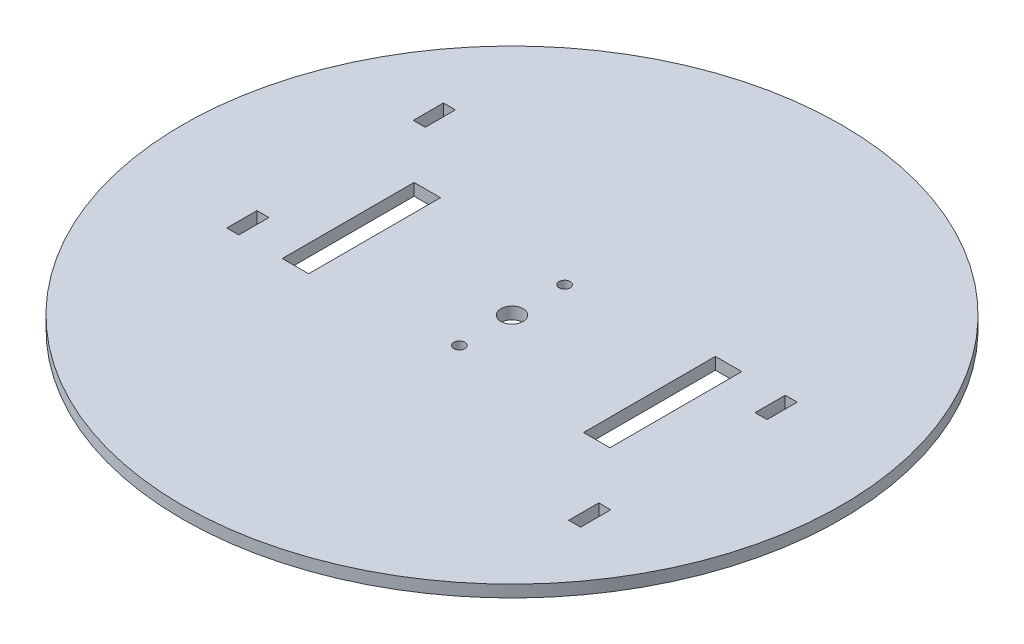
SolidWorks part; units mm, degrees
ref_plane "Front Plane" through (0, 0, 0) normal (0, 0, 1) x (1, 0, 0)
ref_plane "Top Plane" through (0, 0, 0) normal (0, 1, 0) x (1, 0, 0)
ref_plane "Right Plane" through (0, 0, 0) normal (1, 0, 0) x (0, 0, -1)
sketch "Sketch1" plane through (0, 0, 0) normal (0, 1, 0) x (1, 0, 0)
  circle A0 centre (0, 0) radius 87.5
  dimension "D1" = 175
extrude "Boss-Extrude1" add sketch "Sketch1" along normal blind 3.18
sketch "Sketch2" plane through (0, 3.18, 0) normal (0, 1, 0) x (1, 0, 0)
  line L0 (-40, 0) -> (40, 0) construction
  line L2 (0, 58.7688) -> (0, -27.7699) construction
  line L3 (-43.5, 17.5) -> (-36.5, 17.5)
  line L4 (-43.5, 17.5) -> (-43.5, -17.5)
  line L5 (-43.5, -17.5) -> (-36.5, -17.5)
  line L6 (-36.5, 17.5) -> (-36.5, -17.5)
  line L7 (-43.5, 17.5) -> (-36.5, -17.5) construction
  line L8 (-43.5, -17.5) -> (-36.5, 17.5) construction
  line L9 (36.5, 17.5) -> (43.5, 17.5)
  line L10 (36.5, 17.5) -> (36.5, -17.5)
  line L11 (36.5, -17.5) -> (43.5, -17.5)
  line L12 (43.5, 17.5) -> (43.5, -17.5)
  line L13 (36.5, 17.5) -> (43.5, -17.5) construction
  line L14 (36.5, -17.5) -> (43.5, 17.5) construction
  circle A0 centre (0, 0) radius 87.5 construction
  point P13 (-87.5, 0)
  point P14 (87.5, 0)
  dimension "D1" = 80
  dimension "D2" = 7
  dimension "D3" = 7
  dimension "D4" = 35
  dimension "D5" = 35
extrude "Cut-Extrude1" cut sketch "Sketch2" against normal blind 3.18
sketch "Sketch3" plane through (0, 0, 0) normal (0, -1, 0) x (1, 0, 0)
  line L0 (0, 0) -> (87.5, 0) construction
  line L1 (40, -17.5) -> (40, 0) construction
  line L2 (43.5, -17.5) -> (36.5, -17.5) construction
  line L3 (40, -17.5) -> (85.7321, -17.5) construction
  line L4 (56.29, -13.84) -> (56.29, 35.66) construction
  line L5 (54.7, -17.84) -> (57.88, -17.84)
  line L6 (54.7, -17.84) -> (54.7, -9.84)
  line L7 (54.7, -9.84) -> (57.88, -9.84)
  line L8 (57.88, -17.84) -> (57.88, -9.84)
  line L9 (54.7, -17.84) -> (57.88, -9.84) construction
  line L10 (54.7, -9.84) -> (57.88, -17.84) construction
  line L11 (0, 0) -> (0, 87.5) construction
  line L12 (57.88, 31.66) -> (54.7, 31.66)
  line L13 (57.88, 31.66) -> (57.88, 39.66)
  line L14 (57.88, 39.66) -> (54.7, 39.66)
  line L15 (54.7, 31.66) -> (54.7, 39.66)
  line L16 (57.88, 31.66) -> (54.7, 39.66) construction
  line L17 (57.88, 39.66) -> (54.7, 31.66) construction
  line L18 (-40, 17.5) -> (-40, 0) construction
  line L19 (-40, 0) -> (-87.5, 0) construction
  line L20 (-56.29, 13.84) -> (-56.29, -35.66) construction
  line L35 (-43.5, 17.5) -> (-36.5, 17.5) construction
  line L36 (-40, 17.5) -> (-85.7321, 17.5) construction
  line L37 (-54.7, 17.84) -> (-57.88, 17.84)
  line L38 (-54.7, 17.84) -> (-54.7, 9.84)
  line L39 (-54.7, 9.84) -> (-57.88, 9.84)
  line L40 (-57.88, 17.84) -> (-57.88, 9.84)
  line L41 (-54.7, 17.84) -> (-57.88, 9.84) construction
  line L42 (-54.7, 9.84) -> (-57.88, 17.84) construction
  line L44 (-54.7, -31.66) -> (-57.88, -31.66)
  line L45 (-54.7, -31.66) -> (-54.7, -39.66)
  line L46 (-54.7, -39.66) -> (-57.88, -39.66)
  line L47 (-57.88, -31.66) -> (-57.88, -39.66)
  line L48 (-54.7, -31.66) -> (-57.88, -39.66) construction
  line L49 (-54.7, -39.66) -> (-57.88, -31.66) construction
  circle A1 centre (0, 0) radius 87.5 construction
  point P11 (56.29, -13.84)
  point P22 (-56.29, 13.84)
  dimension "D1" = 8
  dimension "D2" = 14.7
  dimension "D3" = 3.18
  dimension "D4" = 41.5
  dimension "D5" = 0.34
  dimension "D6" = 8
  dimension "D7" = 3.18
  dimension "D8" = 8
  dimension "D9" = 14.7
  dimension "D10" = 0.34
  dimension "D11" = 8
  dimension "D12" = 41.5
  dimension "D13" = 3.18
  dimension "D14" = 3.18
sketch "Sketch7" plane through (0, 0, 0) normal (0, -1, 0) x (1, 0, 0)
  circle A0 centre (0, 0) radius 2.95
  dimension "D1" = 5.9
extrude "Cut-Extrude5" cut sketch "Sketch7" against normal blind 10 contours A0
sketch "Sketch8" plane through (0, 3.18, 0) normal (0, 1, 0) x (1, 0, 0)
  circle A0 centre (0, 13.975) radius 1.47
  circle A1 centre (0, -13.975) radius 1.47
extrude "Cut-Extrude6" cut sketch "Sketch8" against normal through all
extrude "Cut-Extrude13" cut sketch "Sketch3" against normal through all
